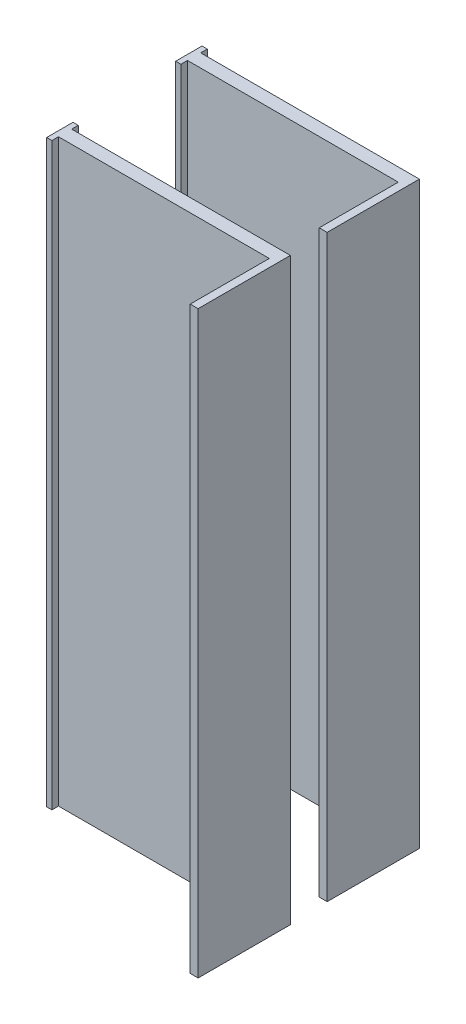
SolidWorks part; units mm, degrees
ref_plane "前视基准面" through (0, 0, 0) normal (0, 0, 1) x (1, 0, 0)
ref_plane "上视基准面" through (0, 0, 0) normal (0, 1, 0) x (1, 0, 0)
ref_plane "右视基准面" through (0, 0, 0) normal (1, 0, 0) x (0, 0, -1)
sketch "草图1" plane through (0, 0, 0) normal (0, 1, 0) x (1, 0, 0)
  line L0 (-40, 2.5) -> (-40, 5)
  line L1 (-40, 2.5) -> (40, 2.5)
  line L3 (-40, -2.5) -> (40, -2.5)
  line L5 (-40, 2.5) -> (40, -2.5) construction
  line L6 (-40, -2.5) -> (40, 2.5) construction
  line L7 (-39.4049, -47.0545) -> (40.5951, -47.0545)
  line L9 (-39.4049, -52.0545) -> (40.5951, -52.0545)
  line L11 (-39.4049, -47.0545) -> (40.5951, -52.0545) construction
  line L12 (-39.4049, -52.0545) -> (40.5951, -47.0545) construction
  line L13 (-40, 5) -> (-42, 5)
  line L17 (-42, 5) -> (-42, -5)
  line L18 (-39.4049, -47.0545) -> (-39.4049, -44.5545)
  line L19 (-39.4049, -44.5545) -> (-41.4049, -44.5545)
  line L20 (-41.4049, -44.5545) -> (-41.4049, -54.5545)
  line L21 (-41.4049, -54.5545) -> (-39.4049, -54.5545)
  line L22 (-39.4049, -54.5545) -> (-39.4049, -52.0545)
  line L23 (40, 2.5) -> (43, 2.5)
  line L24 (43, 2.5) -> (43, -32.5)
  line L25 (43, -32.5) -> (40, -32.5)
  line L26 (40, -32.5) -> (40, -2.5)
  line L27 (40.5951, -47.0545) -> (43.5951, -47.0545)
  line L28 (43.5951, -47.0545) -> (43.5951, -82.0545)
  line L29 (43.5951, -82.0545) -> (40.5951, -82.0545)
  line L30 (40.5951, -82.0545) -> (40.5951, -52.0545)
  line L31 (-42, -5) -> (-40, -5)
  line L32 (-40, -5) -> (-40, -2.5)
  point P0 (0, 0)
  point P5 (0.5951, -49.5545)
  dimension "D1" = 80
  dimension "D2" = 5
  dimension "D3" = 80
  dimension "D4" = 5
extrude "凸台-拉伸1" add sketch "草图1" along normal blind 220
